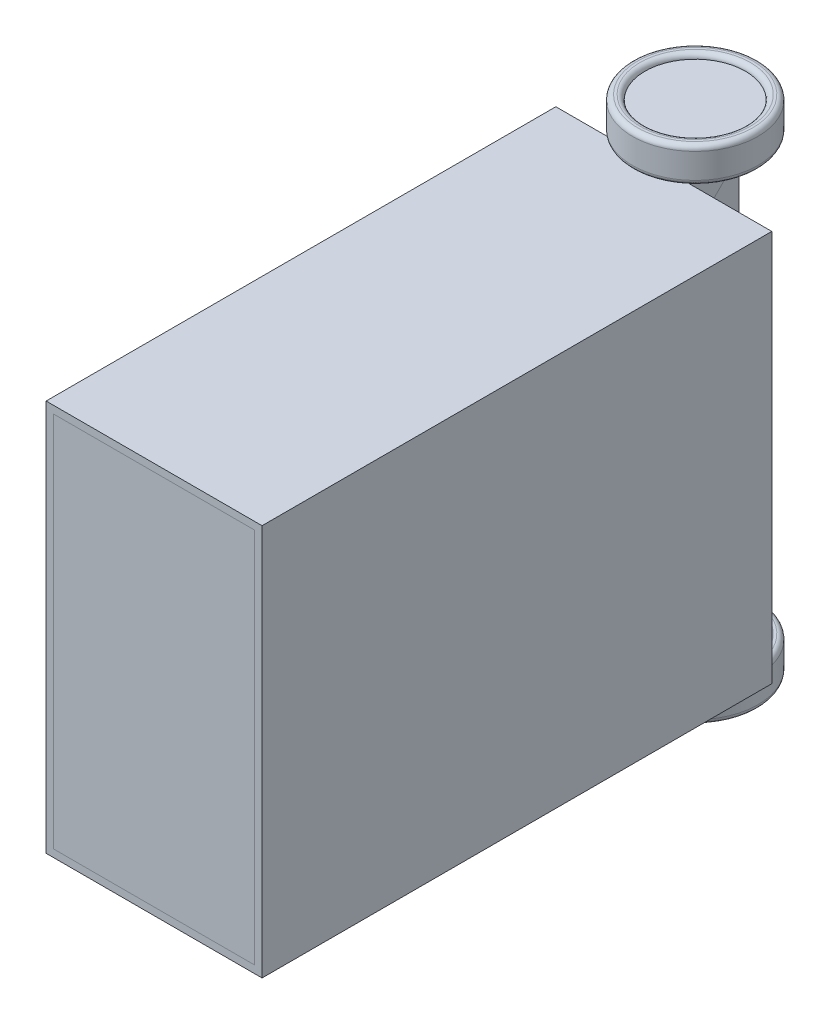
SolidWorks part; units mm, degrees
ref_plane "Ebene vorne" through (0, 0, 0) normal (1, 0, 0) x (0, 1, 0)
ref_plane "Ebene oben" through (0, 0, 0) normal (0, 0, 1) x (0, 1, 0)
ref_plane "Ebene rechts" through (0, 0, 0) normal (0, 1, 0) x (-1, 0, 0)
sketch "Skizze1" plane through (0, 0, 0) normal (0, 0, 1) x (0, 1, 0)
  line L1 (-75, -40) -> (75, -40)
  line L2 (-75, -40) -> (-75, 40)
  line L3 (-75, 40) -> (75, 40)
  line L4 (75, -40) -> (75, 40)
  line L5 (-75, -40) -> (75, 40) construction
  line L6 (-75, 40) -> (75, -40) construction
  point P0 (0, 0)
  dimension "D1" = 80
  dimension "D2" = 150
extrude "Aufsatz-Linear austragen1" add sketch "Skizze1" along normal blind 3
move or copy body "Körper-Verschieben/Kopieren1" bodies to move or copy 101 copy yes number of copies 1 translate (0, 0, 40) parameters "D1"=0, "D2"=0, "D3"=40
move or copy body "Körper-Verschieben/Kopieren2" bodies to move or copy 102 copy yes number of copies 1 translate (0, 0, 100) parameters "D1"=0, "D2"=0, "D3"=100
move or copy body "Körper-Verschieben/Kopieren3" bodies to move or copy 103 copy yes number of copies 1 translate (0, 0, 30) parameters "D1"=0, "D2"=0, "D3"=30
move or copy body "Körper-Verschieben/Kopieren4" bodies to move or copy 104 copy yes number of copies 1 translate (0, 0, 30) parameters "D1"=0, "D2"=0, "D3"=30
sketch "Skizze2" plane through (0, 0, 0) normal (0, 0, -1) x (1, 0, 0)
  line L0 (-43, -78) -> (43, -78)
  line L1 (43, -78) -> (43, 78)
  line L2 (43, 78) -> (-43, 78)
  line L3 (-43, 78) -> (-43, -78)
  line L4 (-40, -75) -> (40, -75)
  line L5 (40, -75) -> (40, 75)
  line L6 (40, 75) -> (-40, 75)
  line L7 (-40, 75) -> (-40, -75)
  line L8 (-40, -75) -> (40, -75)
  line L9 (40, -75) -> (40, 75)
  line L10 (40, 75) -> (-40, 75)
  line L11 (-40, 75) -> (-40, -75)
  dimension "D1" = 0
  dimension "D2" = 3
extrude "Aufsatz-Linear austragen2" add sketch "Skizze2" against normal up to vertex separate body
sketch "Skizze3" plane through (0, 0, 0) normal (0, 0, -1) x (1, 0, 0)
  line L0 (-43, -78) -> (43, -78) construction
  line L1 (-10, 78) -> (10, 78)
  line L2 (-10, 78) -> (-10, 58)
  line L3 (-10, 58) -> (10, 58)
  line L4 (10, 78) -> (10, 58)
  line L5 (-10, -58) -> (10, -58)
  line L6 (-10, -58) -> (-10, -78)
  line L7 (-10, -78) -> (10, -78)
  line L8 (10, -58) -> (10, -78)
  line L9 (43, 78) -> (-43, 78) construction
  point P8 (0, 58)
  point P9 (0, -58)
  point P11 (15.8847, -78)
  point P14 (15.6641, 78)
  dimension "D1" = 20
extrude "Aufsatz-Linear austragen3" add sketch "Skizze3" along normal blind 20 separate body
sketch "Skizze4" plane through (0, -78, 0) normal (0, -1, 0) x (1, 0, 0)
  line L0 (-10, 0) -> (15, -20) construction
  line L1 (10, -20) -> (-10, -20) construction
  circle A0 centre (2.5, -10) radius 4
  dimension "D1" = 8
extrude "Aufsatz-Linear austragen4" add sketch "Skizze4" along normal blind 10 separate body
sketch "Skizze5" plane through (0, -88, 0) normal (0, -1, 0) x (1, 0, 0)
  circle A0 centre (2.5, -10) radius 20
  dimension "D1" = 40
extrude "Aufsatz-Linear austragen5" add sketch "Skizze5" along normal blind 10 separate body
ref_plane "Ebene1" through (0, -93, 0) normal (0, -1, 0) x (-1, 0, 0)
sketch "Skizze7" plane through (0, -93, 0) normal (0, -1, 0) x (-1, 0, 0)
  circle A0 centre (-2.5, 10) radius 20 construction
  circle A1 centre (-2.5, 10) radius 20
  circle A2 centre (-2.5, 10) radius 25
  dimension "D1" = 5
extrude "Aufsatz-Linear austragen6" add sketch "Skizze7" along normal mid plane 14 separate body
fillet "Verrundung1" radius 2 4 edges at (2.5, -86, -30) (2.5, -86, -35) (2.5, -100, -30) (2.5, -100, -35)
mirror "Spiegeln1" about plane through (0, 0, 0) normal (0, 1, 0) of bodies 107 109 111 110
sketch "Skizze8" plane through (0, 0, 43) normal (0, 0, 1) x (1, 0, 0)
  line L1 (-31.3961, 65.9035) -> (31.3961, 65.9035)
  line L2 (-31.3961, 65.9035) -> (-31.3961, -65.9035)
  line L3 (-31.3961, -65.9035) -> (31.3961, -65.9035)
  line L4 (31.3961, 65.9035) -> (31.3961, -65.9035)
  line L5 (-31.3961, 65.9035) -> (31.3961, -65.9035) construction
  line L6 (-31.3961, -65.9035) -> (31.3961, 65.9035) construction
  point P0 (0, 0)
extrude "Aufsatz-Linear austragen7" add sketch "Skizze8" along normal blind 2 from offset 5 separate body
sketch "Skizze9" plane through (0, 0, 0) normal (1, 0, 0) x (0, 1, 0)
  circle A0 centre (-22.6, 186.213) radius 8.5082
  circle A1 centre (-5.5837, 186.213) radius 8.5082
  circle A2 centre (11.4327, 186.213) radius 8.5082
  point P6 (0, 0)
  point P7 (11.4327, 186.213)
extrude "Aufsatz-Linear austragen8" add sketch "Skizze9" along normal mid plane 50 separate body contours A0 | A1 | A2
